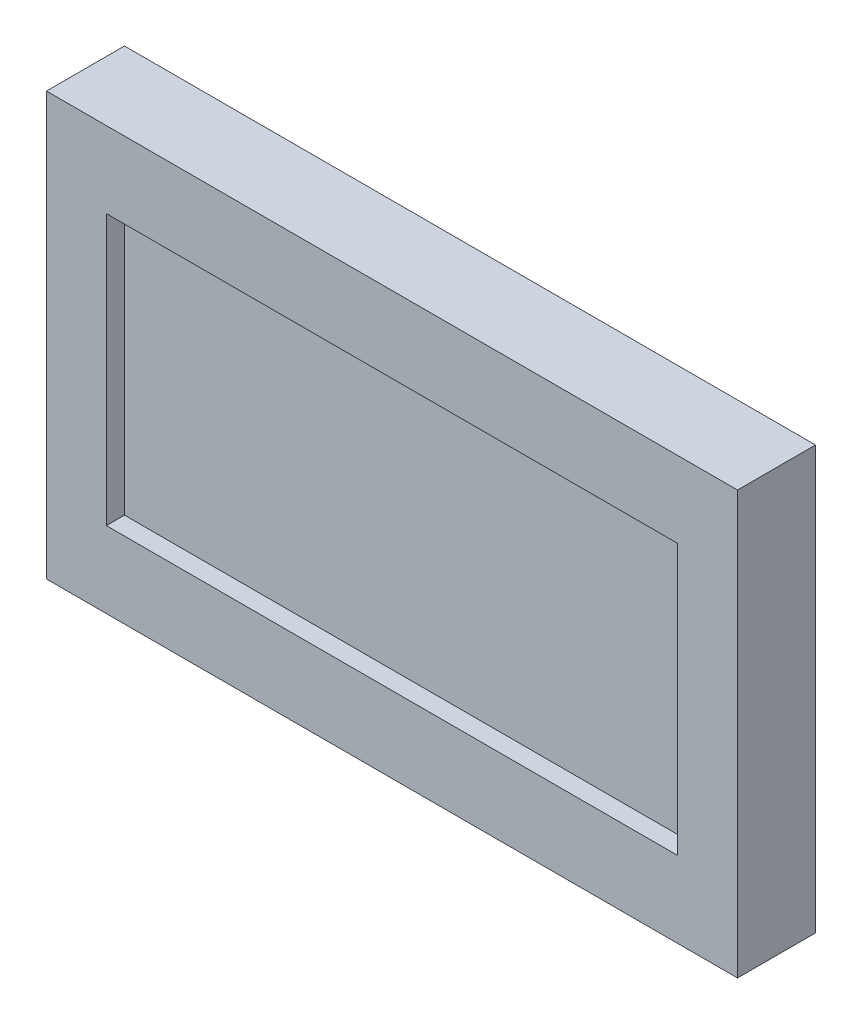
SolidWorks part; units mm, degrees
ref_plane "Přední rovina" through (0, 0, 0) normal (0, 0, 1) x (1, 0, 0)
ref_plane "Horní rovina" through (0, 0, 0) normal (0, 1, 0) x (1, 0, 0)
ref_plane "Pravá rovina" through (0, 0, 0) normal (1, 0, 0) x (0, 0, -1)
sketch "Skica1" plane through (0, 0, 0) normal (0, 0, 1) x (1, 0, 0)
  line L1 (-19.05, -11.65) -> (19.05, -11.65)
  line L2 (-19.05, -11.65) -> (-19.05, 11.65)
  line L3 (-19.05, 11.65) -> (19.05, 11.65)
  line L4 (19.05, -11.65) -> (19.05, 11.65)
  line L5 (-19.05, -11.65) -> (19.05, 11.65) construction
  line L6 (-19.05, 11.65) -> (19.05, -11.65) construction
  point P0 (0, 0)
  dimension "D1" = 38.1
  dimension "D2" = 23.3
extrude "Přidat vysunutím1" add sketch "Skica1" along normal blind 4.3
sketch "Skica2" plane through (0, 0, 4.3) normal (0, 0, 1) x (1, 0, 0)
  line L0 (19.05, -11.65) -> (19.05, 11.65) construction
  line L1 (-15.75, -7.45) -> (15.75, -7.45)
  line L2 (-15.75, -7.45) -> (-15.75, 7.45)
  line L3 (-15.75, 7.45) -> (15.75, 7.45)
  line L4 (15.75, -7.45) -> (15.75, 7.45)
  line L5 (-15.75, -7.45) -> (15.75, 7.45) construction
  line L6 (-15.75, 7.45) -> (15.75, -7.45) construction
  line L7 (-19.05, -11.65) -> (19.05, -11.65) construction
  point P0 (0, 0)
  dimension "D1" = 3.3
  dimension "D2" = 4.2
extrude "Odebrat vysunutím1" cut sketch "Skica2" against normal blind 4.3
sketch "Skica3" plane through (0, 0, 0) normal (0, 0, -1) x (-1, 0, 0)
  line L1 (17.1916, 9.8512) -> (-17.1916, 9.8512)
  line L2 (17.1916, 9.8512) -> (17.1916, -9.8512)
  line L3 (17.1916, -9.8512) -> (-17.1916, -9.8512)
  line L4 (-17.1916, 9.8512) -> (-17.1916, -9.8512)
  line L5 (17.1916, 9.8512) -> (-17.1916, -9.8512) construction
  line L6 (17.1916, -9.8512) -> (-17.1916, 9.8512) construction
  point P0 (0, 0)
extrude "Odebrat vysunutím2" cut sketch "Skica3" against normal blind 3.3
sketch "Skica6" plane through (0, 0, 3.3) normal (0, 0, -1) x (-1, 0, 0)
  line L1 (15.75, -7.45) -> (-15.75, -7.45)
  line L2 (15.75, -7.45) -> (15.75, 7.45)
  line L3 (15.75, 7.45) -> (-15.75, 7.45)
  line L4 (-15.75, -7.45) -> (-15.75, 7.45)
extrude "Přidat vysunutím3" add sketch "Skica6" along normal up to vertex (3.3 mm away) separate body
